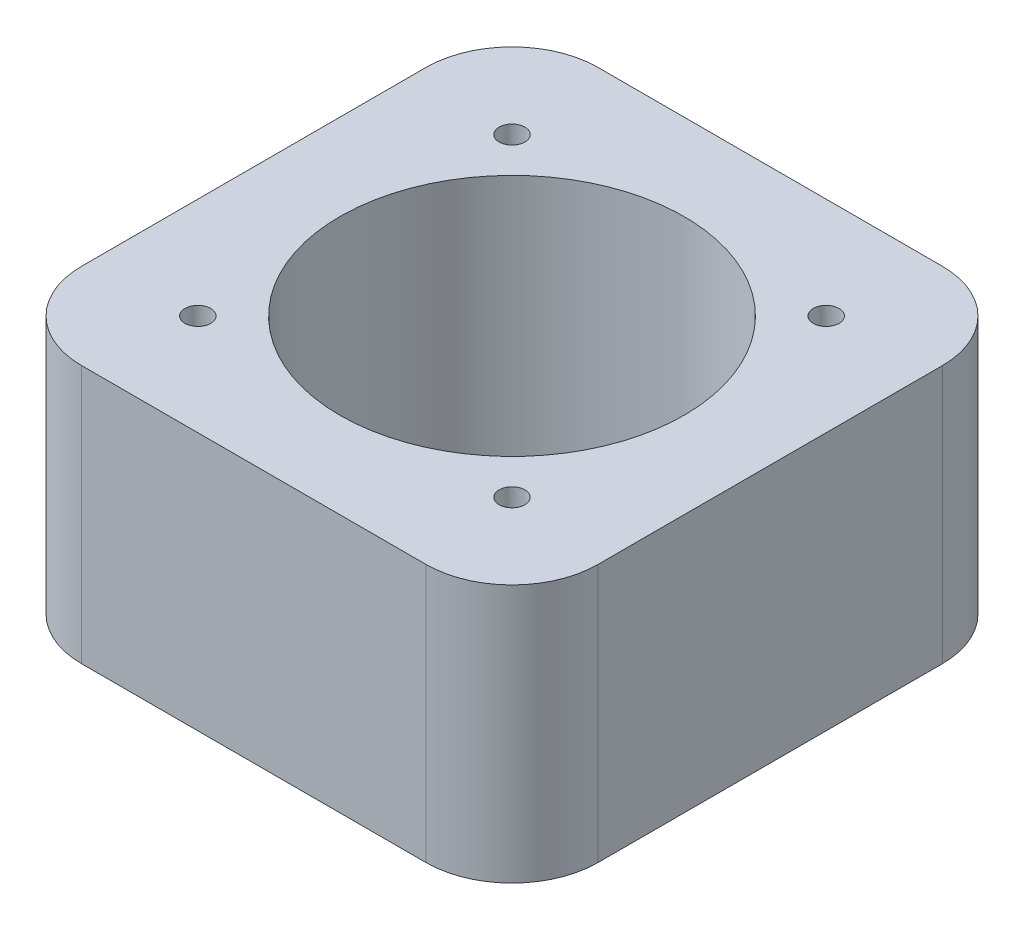
SolidWorks part; units mm, degrees
material "Polybutadiene (PB)"
ref_plane "Front Plane" through (0, 0, 0) normal (0, 0, 1) x (1, 0, 0)
ref_plane "Top Plane" through (0, 0, 0) normal (0, 1, 0) x (1, 0, 0)
ref_plane "Right Plane" through (0, 0, 0) normal (1, 0, 0) x (0, 0, -1)
sketch "Sketch1" plane through (0, 0, 0) normal (0, 1, 0) x (1, 0, 0)
  line L0 (30, 60) -> (30, 0) construction
  line L1 (0, 0) -> (60, 0)
  line L2 (0, 0) -> (0, 60)
  line L3 (0, 60) -> (60, 60)
  line L4 (60, 0) -> (60, 60)
  line L5 (11.75, 48.25) -> (11.75, 11.75) construction
  line L6 (11.75, 11.75) -> (48.25, 11.75) construction
  line L7 (48.25, 11.75) -> (48.25, 48.25) construction
  line L8 (48.25, 48.25) -> (11.75, 48.25) construction
  line L9 (48.25, 30) -> (11.75, 30) construction
  circle A0 centre (30, 30) radius 20
  circle A1 centre (48.25, 48.25) radius 1.5
  circle A2 centre (11.75, 48.25) radius 1.5
  circle A3 centre (11.75, 11.75) radius 1.5
  circle A4 centre (48.25, 11.75) radius 1.5
  dimension "D3" = 40
  dimension "D4" = 3
  dimension "D5" = 36.5
  dimension "D1" = 60
  dimension "D2" = 60
extrude "Boss-Extrude1" add sketch "Sketch1" along normal blind 30
fillet "Fillet1" radius 10 4 edges at (60, 15, 0) (0, 15, 0) (0, 15, -60) (60, 15, -60)
sketch "Sketch2" plane through (0, 0, 0) normal (-1, 0, 0) x (0, 0, 1)
  line L0 (-50, 15) -> (-10, 15) construction
  line L1 (-48.75, 15) -> (-50, 15) construction
  line L2 (-50, 30) -> (-50, 0) construction
  line L3 (-10, 0) -> (-10, 30) construction
  line L4 (-48.75, 15) -> (-11.25, 15) construction
  line L5 (-11.25, 15) -> (-10, 15) construction
  line L6 (-34.062, 19.75) -> (-34.062, 10.25) construction
  line L7 (-25.938, 19.75) -> (-25.938, 10.25) construction
  line L8 (-49.8397, 17.25) -> (-49.8397, 12.75) construction
  line L9 (-10.1603, 17.25) -> (-10.1603, 12.75) construction
  line L10 (-49.8397, 17.25) -> (-34.062, 19.75)
  line L11 (-49.8397, 12.75) -> (-34.062, 10.25)
  line L12 (-25.938, 19.75) -> (-10.1603, 17.25)
  line L13 (-25.938, 10.25) -> (-10.1603, 12.75)
  circle A0 centre (-30, 15) radius 6.25
  circle A1 centre (-48.75, 15) radius 2.5
  circle A2 centre (-11.25, 15) radius 2.5
  line M5 (-10, 0) -> (-10, 30)
  line M7 (-50, 30) -> (-50, 0)
  dimension "D1" = 12.5
  dimension "D4" = 5
  dimension "D2" = 37.5
  dimension "D3" = 0
  dimension "D5" = 9.5
  dimension "D6" = 4.5
extrude "Cut-Extrude1" cut sketch "Sketch2" against normal blind 5 contours A1 L11 A0 L10 | A0 | A2 L12 A0 L13 | A2 L12 L13 M5 | A2 M5 | L10 A1 L11 M7 | A1 M7
sketch "Sketch3" plane through (5, 0, 0) normal (-1, 0, 0) x (0, 0, 1)
  line L0 (-30, 21.25) -> (-30, 8.75) construction
  arc A0 (-25.938, 19.75) -> (-34.062, 19.75) centre (-30, 15) ccw construction
  arc A1 (-34.062, 10.25) -> (-25.938, 10.25) centre (-30, 15) ccw construction
  circle A2 centre (-30, 15) radius 2.5
  dimension "D1" = 5
extrude "Cut-Extrude4" cut sketch "Sketch3" against normal blind 1
sketch "Sketch4" plane through (5, 0, 0) normal (-1, 0, 0) x (0, 0, 1)
  line L0 (-51.25, 15) -> (-8.75, 15) construction
  line L1 (-30, 15) -> (-48, 15) construction
  line L2 (-30, 15) -> (-12, 15) construction
  arc A0 (-49.8397, 17.25) -> (-49.8397, 12.75) centre (-48.75, 15) ccw construction
  arc A1 (-10.1603, 12.75) -> (-10.1603, 17.25) centre (-11.25, 15) ccw construction
  circle A2 centre (-12, 15) radius 0.5
  circle A3 centre (-48, 15) radius 0.5
  dimension "D3" = 1
  dimension "D1" = 18
  dimension "D2" = 18
extrude "Cut-Extrude5" cut sketch "Sketch4" against normal blind 2
